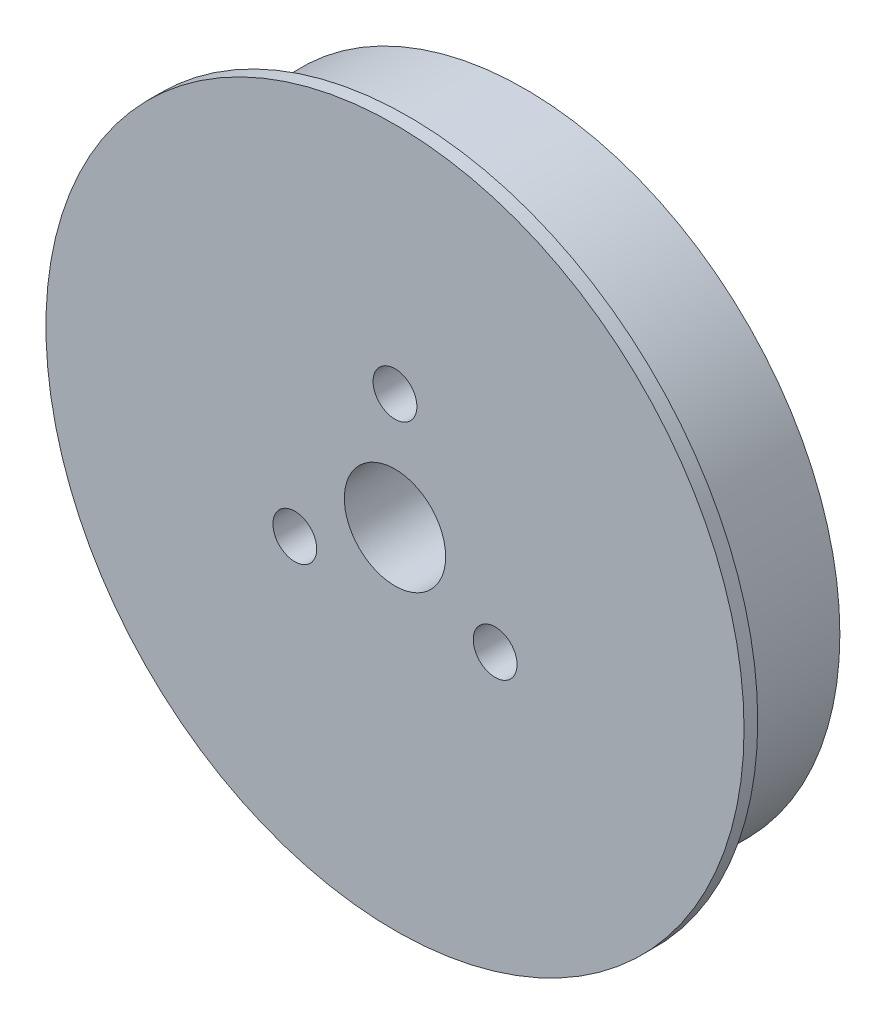
SolidWorks part; units mm, degrees
other "Rim-Inside" parameters "D1"=11.4465, "D2"=30.9038, "D3"=3.4737, "D4"=12.1609
ref_plane "Front Plane" through (0, 0, 0) normal (0, 0, 1) x (1, 0, 0)
ref_plane "Top Plane" through (0, 0, 0) normal (0, 1, 0) x (1, 0, 0)
ref_plane "Right Plane" through (0, 0, 0) normal (1, 0, 0) x (0, 0, -1)
sketch "Sketch1" plane through (0, 0, 0) normal (0, 0, 1) x (1, 0, 0)
  circle A0 centre (0, 0) radius 3.7
  circle A1 centre (0, 0) radius 23
  circle A5 centre (0, 0) radius 18
  dimension "D1" = 7.4
  dimension "D2" = 46
  dimension "D4" = 36
extrude "Boss-Extrude1" add sketch "Sketch1" along normal blind 9.5
sketch "Sketch9" plane through (0, 0, 9.5) normal (0, 0, 1) x (1, 0, 0)
  circle A0 centre (0, 0) radius 25.5
  circle A1 centre (0, 0) radius 23 construction
  circle M2 centre (0, 0) radius 23
  dimension "D1" = 51
extrude "Boss-Extrude3" add sketch "Sketch9" against normal blind 1 contours A0 M2
sketch "Sketch6" plane through (0, 0, 0) normal (0, 0, -1) x (-1, 0, 0)
  line L0 (0, 0) -> (0, 8.45) construction
  line L1 (0, 0) -> (7.3179, -4.225) construction
  line L2 (0, 0) -> (-7.3179, -4.225) construction
  dimension "D2" = 8.45
  dimension "D1" = 3
hole_wizard "Hole1" positions "3DSketch2" profile "Sketch8" legacy
sketch3d "3DSketch2"
  point P0 (0, 8.45, 0)
  point P3 (7.3179, -4.225, 0)
  point P6 (-7.3179, -4.225, 0)
sketch "Sketch8" plane through (0, 8.45, 0) normal (1, 0, 0) x (0, 1, 0)
  line L0 (0, 0) -> (0, 9.499)
  line L1 (0, 9.499) -> (1.6, 9.499)
  line L2 (1.6, 9.499) -> (1.6, 0)
  line L3 (1.6, 0) -> (0, 0)
  line L4 (0, 110) -> (0, -10) construction
  dimension "Diameter" = 3.2
  dimension "Depth" = 9.499
equation "\"M3 Nut Diameter\" = 5.50mm"
equation "\"Clearance Diameter 3D Printing\" = .20mm"
equation "\"D-Shaft\"= 4mm'D-Shaft diameter"
equation "\"Wheel Axle Diameter\"= 6.8mm'Axle to Connect to Wheel"
equation "\"Wheel Thickness\"= 10mm'Wheel Thickness"
equation "\"M3 Screw Diameter\"= 3.20mm'M3 Screw Diameter already with 3D printing Clearance"
equation "\"D1@Sketch1\" = \"Wheel Axle Diameter\" + .6mm"
equation "\"Wheel Diameter\"= 60mm"
equation "\"Silicone Tire Width\"= 7mm"
equation "\"D2@Sketch1\"= \"Wheel Diameter\" - 2 * \"Silicone Tire Width\""
equation "\"D2@Sketch6\"= ( \"Wheel Axle Diameter\" / 2 ) + ( ( \"M3 Nut Diameter\" + \"Clearance Diameter 3D Printing\" + .40mm ) / 2 ) + 2mm"
equation "\"D1@Boss-Extrude1\"=\"Wheel Thickness\"-0.5mm"
equation "\"Diameter\"= \"M3 Screw Diameter\""
equation "\"Logo Diameter\"= 36mm"
equation "\"D4@Sketch1\"= \"Logo Diameter\""
